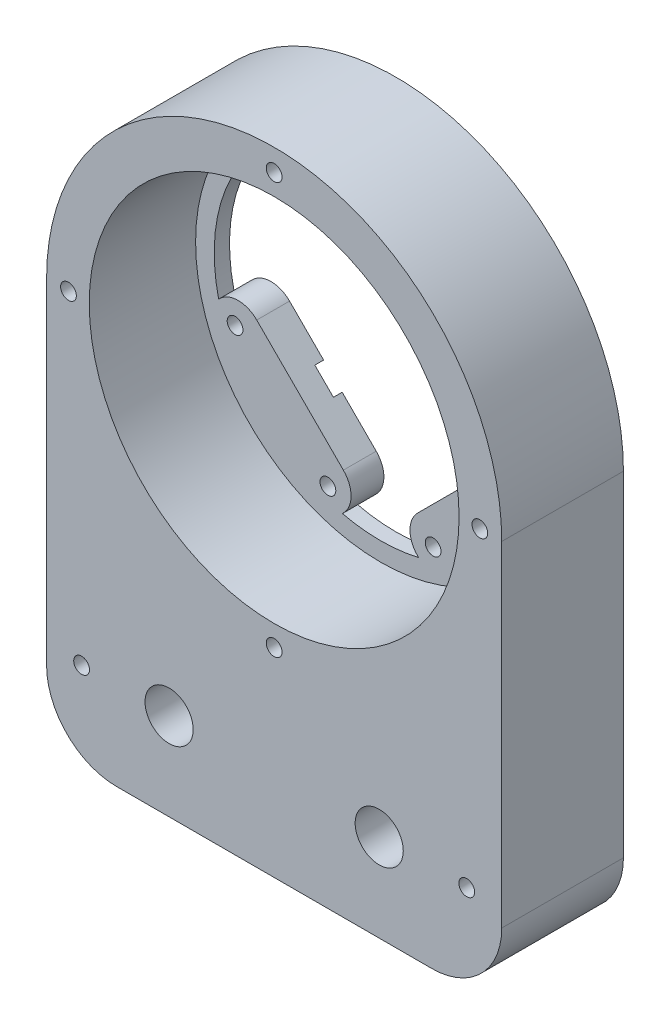
SolidWorks part; units mm, degrees
ref_plane "Спереди" through (0, 0, 0) normal (0, 0, 1) x (1, 0, 0)
ref_plane "Сверху" through (0, 0, 0) normal (0, 1, 0) x (1, 0, 0)
ref_plane "Справа" through (0, 0, 0) normal (1, 0, 0) x (0, 0, -1)
sketch "Эскиз2" plane through (0, 0, 0) normal (0, 0, 1) x (1, 0, 0)
  line L0 (0, 0) -> (0, 0.25)
  line L1 (-26, -10) -> (26, -10) construction
  line L2 (-26, 26.25) -> (26, 26.25)
  line L3 (-26, 26.25) -> (-26, -20)
  line L4 (-26, -20) -> (26, -20)
  line L5 (26, 26.25) -> (26, -20)
  line L6 (0, 26.25) -> (0, -20) construction
  circle A0 centre (0, 26.25) radius 26
  circle A1 centre (0, 26.25) radius 19
  circle A2 centre (-12, -10) radius 2.75
  circle A3 centre (12, -10) radius 2.75
  dimension "D1" = 52
  dimension "D4" = 38
  dimension "D6" = 5.5
  dimension "D2" = 0.25
  dimension "D3" = 20
  dimension "D5" = 10
  dimension "D7" = 24
extrude "Бобышка-Вытянуть1" add sketch "Эскиз2" along normal blind 13.9
sketch "Эскиз3" plane through (0, 0, 13.9) normal (0, 0, 1) x (1, 0, 0)
  circle A0 centre (0, 26.25) radius 21.125
  dimension "D1" = 42.25
extrude "Вырез-Вытянуть1" cut sketch "Эскиз3" against normal blind 12.15
sketch "Эскиз4" plane through (0, 0, 0) normal (0, 0, -1) x (-1, 0, 0)
  circle A0 centre (-12, -10) radius 5
  circle A1 centre (12, -10) radius 5
  dimension "D1" = 10
  dimension "D2" = 10
extrude "Вырез-Вытянуть2" cut sketch "Эскиз4" against normal blind 3
fillet "Скругление1" radius 8 2 edges at (-26, -20, 6.95) (26, -20, 6.95)
sketch "Эскиз5" plane through (0, 0, 13.9) normal (0, 0, 1) x (1, 0, 0)
  line L1 (-18, -20) -> (18, -20) construction
  line L2 (0, 26.25) -> (0, -20) construction
  circle A2 centre (0, 26.25) radius 23.5 construction
  circle A3 centre (0, 26.25) radius 21.125 construction
  circle A4 centre (0, 49.75) radius 0.9
  circle A5 centre (-23.5, 26.25) radius 0.9
  circle A6 centre (0, 2.75) radius 0.9
  circle A7 centre (23.5, 26.25) radius 0.9
  circle A8 centre (-22, -10) radius 0.9
  circle A9 centre (22, -10) radius 0.9
  dimension "D1" = 47
  dimension "D2" = 1.8
  dimension "D6" = 1.8
  dimension "D4" = 10
  dimension "D5" = 44
  dimension "D3" = 4
extrude "Вырез-Вытянуть3" cut sketch "Эскиз5" against normal through all
sketch "Эскиз6" plane through (0, 0, 0) normal (0, 0, -1) x (-1, 0, 0)
  line L0 (-22.6274, 17.7647) -> (-18.3848, 22.0074)
  line L1 (-22.6274, 13.5221) -> (-12.7279, 3.6226)
  line L2 (-14.1421, 22.0074) -> (-4.2426, 12.1079)
  line L3 (-8.4853, 3.6226) -> (-4.2426, 7.8652)
  line L4 (-24.7487, 15.6434) -> (-2.1213, 9.9865) construction
  line L5 (-16.2635, 24.1287) -> (-10.6066, 1.5013) construction
  line L6 (-13.435, 12.815) -> (0, 26.25) construction
  line L7 (0, 26.25) -> (0, 2.75) construction
  line L8 (-16.617, 20.2396) -> (-6.0104, 9.633) construction
  line L9 (14.1421, 22.0074) -> (4.2426, 12.1079)
  line L10 (8.4853, 3.6226) -> (4.2426, 7.8652)
  line L11 (22.6274, 13.5221) -> (12.7279, 3.6226)
  line L12 (22.6274, 17.7647) -> (18.3848, 22.0074)
  circle A0 centre (-16.617, 20.2396) radius 0.9
  circle A1 centre (-6.0104, 9.633) radius 0.9
  arc A2 (-8.4853, 3.6226) -> (-12.7279, 3.6226) centre (-10.6066, 5.7439) cw
  arc A3 (-4.2426, 7.8652) -> (-4.2426, 12.1079) centre (-6.364, 9.9865) ccw
  arc A4 (-14.1421, 22.0074) -> (-18.3848, 22.0074) centre (-16.2635, 19.886) ccw
  arc A5 (-22.6274, 13.5221) -> (-22.6274, 17.7647) centre (-20.5061, 15.6434) cw
  circle A6 centre (6.0104, 9.633) radius 0.9
  circle A7 centre (16.617, 20.2396) radius 0.9
  arc A8 (4.2426, 7.8652) -> (4.2426, 12.1079) centre (6.364, 9.9865) cw
  arc A9 (8.4853, 3.6226) -> (12.7279, 3.6226) centre (10.6066, 5.7439) ccw
  arc A10 (14.1421, 22.0074) -> (18.3848, 22.0074) centre (16.2635, 19.886) cw
  arc A11 (22.6274, 13.5221) -> (22.6274, 17.7647) centre (20.5061, 15.6434) ccw
  point P1 (-13.435, 12.815)
  dimension "D7" = 1.8
  dimension "D8" = 3
  dimension "D1" = 45
  dimension "D2" = 20
  dimension "D3" = 12
  dimension "D4" = 13
  dimension "D5" = 3
  dimension "D6" = 15
extrude "Бобышка-Вытянуть2" add sketch "Эскиз6" along normal blind 2 and the other way up to surface other way up to face at (19, 26.25, 1.75)
sketch "Эскиз7" plane through (0, 0, -2) normal (0, 0, -1) x (-1, 0, 0)
  line L0 (-14.1421, 12.1079) -> (-9.1924, 17.0576) construction
  line L1 (-15.2028, 13.1685) -> (-10.253, 18.1183)
  line L2 (-13.0815, 11.0472) -> (-8.1317, 15.997)
  line L3 (-4.2426, 12.1079) -> (-14.1421, 22.0074) construction
  line L4 (0, 2.75) -> (0, 19.6667) construction
  line L5 (14.1421, 12.1079) -> (9.1924, 17.0576) construction
  line L6 (15.2028, 13.1685) -> (10.253, 18.1183)
  line L7 (13.0815, 11.0472) -> (8.1317, 15.997)
  arc A0 (-15.2028, 13.1685) -> (-13.0815, 11.0472) centre (-14.1421, 12.1079) ccw
  arc A1 (-8.1317, 15.997) -> (-10.253, 18.1183) centre (-9.1924, 17.0576) ccw
  arc A2 (15.2028, 13.1685) -> (13.0815, 11.0472) centre (14.1421, 12.1079) cw
  arc A3 (8.1317, 15.997) -> (10.253, 18.1183) centre (9.1924, 17.0576) cw
  point P2 (-11.6673, 14.5827)
  point P15 (11.6673, 14.5827)
  dimension "D2" = 1.5
  dimension "D1" = 7
  dimension "D3" = 90
extrude "Вырез-Вытянуть4" cut sketch "Эскиз7" against normal blind 1
equation "\"big_bearing_d1\"= 19.9"
equation "\"big_bearing_d2\"= 42"
equation "\"big_bearing_h\"= 11.9"
equation "\"print_offset\"= 0.5"
equation "\"small_bearing_d1\"= 2.9"
equation "\"small_bearing_d2\"= 10"
equation "\"small_bearing_h\"= 4"
equation "\"tube_d\"= 16"
equation "\"small_bearing_distance\"= 2"
equation "\"D1@Эскиз2\"=\"big_bearing_d2\"+5*2"
equation "\"D2@Эскиз2\"=\"print_offset\"/2"
equation "\"D4@Эскиз2\"=\"big_bearing_d2\"-4"
equation "\"D1@Бобышка-Вытянуть1\"=\"big_bearing_h\"+2"
equation "\"D1@Эскиз3\"=\"big_bearing_d2\"+\"print_offset\"/2"
equation "\"D1@Вырез-Вытянуть1\"=\"big_bearing_h\"+\"print_offset\"/2"
equation "\"D2@Эскиз4\"=\"D1@Эскиз4\""
equation "\"D6@Эскиз5\"=\"D2@Эскиз5\""
